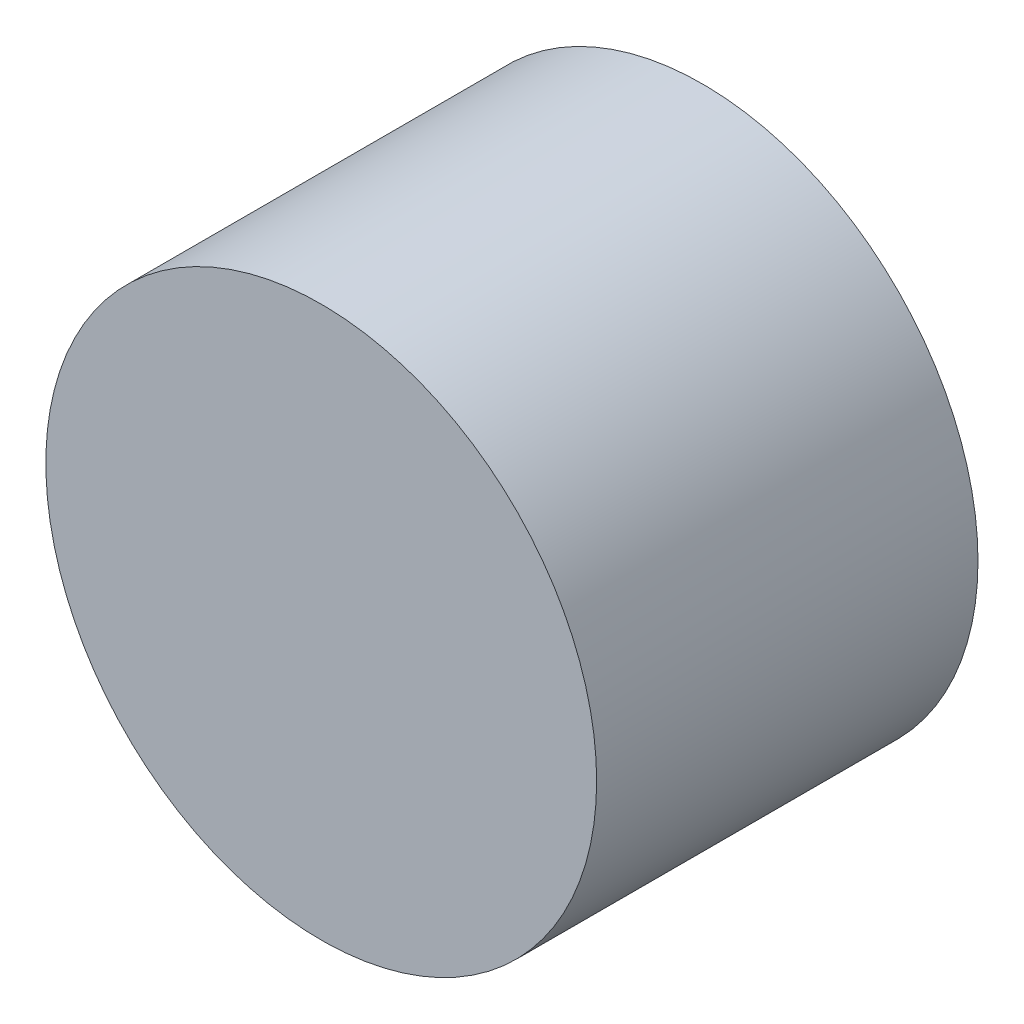
SolidWorks part; units mm, degrees
ref_plane "Plan de face" through (0, 0, 0) normal (0, 0, 1) x (1, 0, 0)
ref_plane "Plan de dessus" through (0, 0, 0) normal (0, 1, 0) x (1, 0, 0)
ref_plane "Plan de droite" through (0, 0, 0) normal (1, 0, 0) x (0, 0, -1)
sketch "Esquisse1" plane through (0, 0, 0) normal (0, 0, 1) x (1, 0, 0)
  circle A0 centre (0, 0) radius 6.5
extrude "Boss.-Extru.1" add sketch "Esquisse1" along normal blind 9
